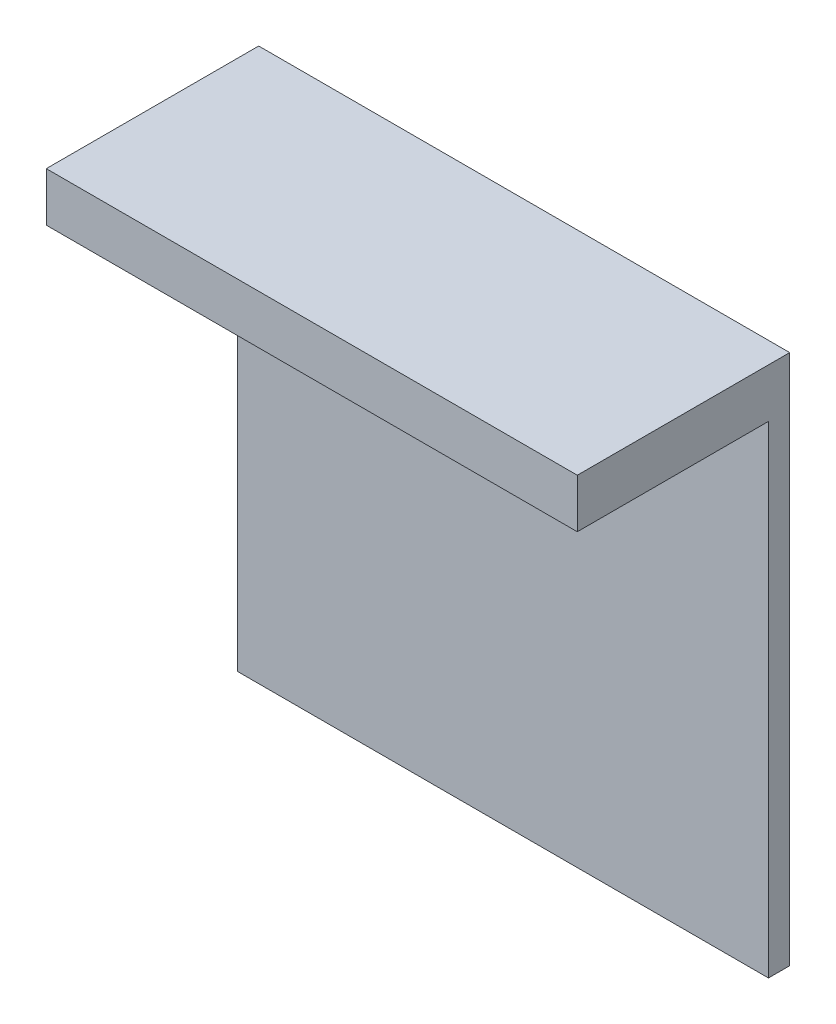
SolidWorks part; units mm, degrees
ref_plane "Front Plane" through (0, 0, 0) normal (0, 0, 1) x (1, 0, 0)
ref_plane "Top Plane" through (0, 0, 0) normal (0, 1, 0) x (1, 0, 0)
ref_plane "Right Plane" through (0, 0, 0) normal (1, 0, 0) x (0, 0, -1)
sketch "Sketch1" plane through (0, 0, 0) normal (0, 1, 0) x (1, 0, 0)
  line L1 (-250, -100) -> (250, -100)
  line L2 (-250, -100) -> (-250, 100)
  line L3 (-250, 100) -> (250, 100)
  line L4 (250, -100) -> (250, 100)
  line L5 (-250, -100) -> (250, 100) construction
  line L6 (-250, 100) -> (250, -100) construction
  point P0 (0, 0)
  dimension "D1" = 500
  dimension "D2" = 200
extrude "Boss-Extrude1" add sketch "Sketch1" against normal blind 500
sketch "Sketch2" plane through (0, 0, 100) normal (0, 0, 1) x (1, 0, 0)
  line L0 (250, -500) -> (250, 0) construction
  line L1 (-250, -500) -> (250, -500)
  line L2 (-250, -500) -> (-250, -46.1102)
  line L3 (-250, -46.1102) -> (250, -46.1102)
  line L4 (250, -500) -> (250, -46.1102)
extrude "Cut-Extrude1" cut sketch "Sketch2" against normal blind 180
